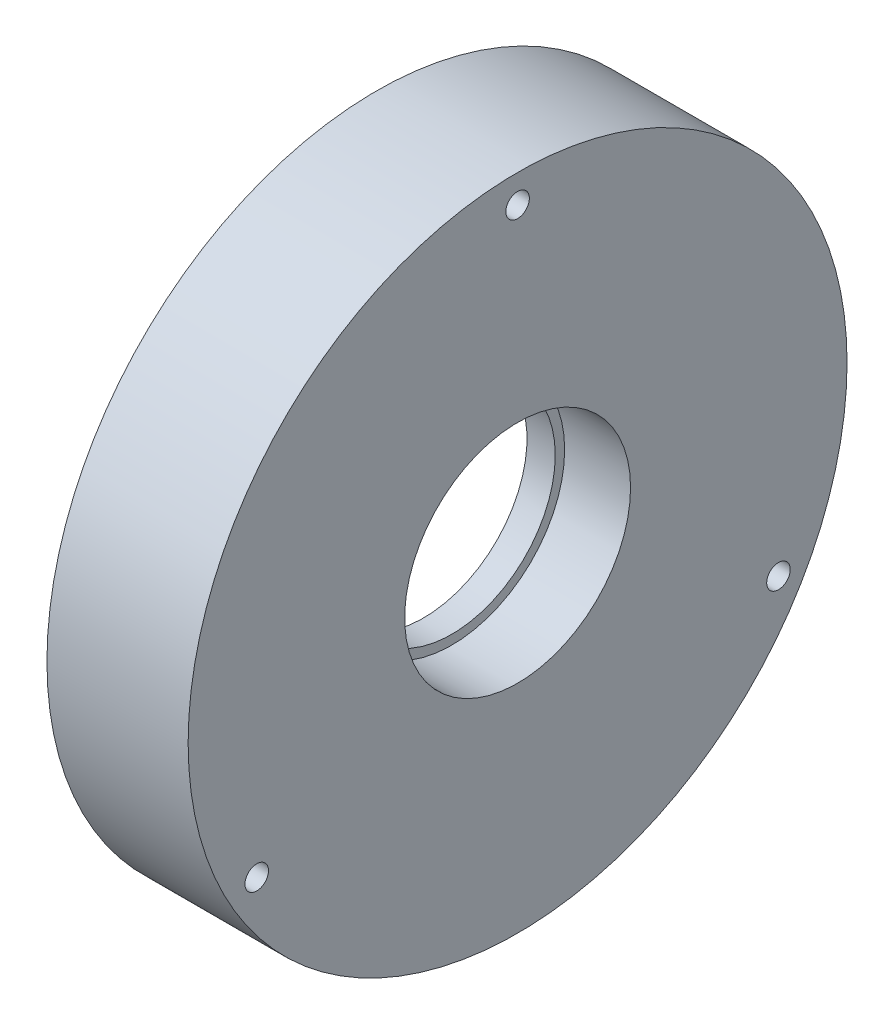
SolidWorks part; units mm, degrees
ref_plane "Plane1" through (0, 0, 0) normal (0, 0, 1) x (1, 0, 0)
ref_plane "Plane2" through (0, 0, 0) normal (0, 1, 0) x (1, 0, 0)
ref_plane "Plane3" through (0, 0, 0) normal (1, 0, 0) x (0, 0, -1)
sketch "HoldingSke" plane through (0, 0, 0) normal (0, 1, 0) x (1, 0, 0)
  line L0 (0, 0) -> (1.1472, -1.6383)
  line L1 (-15, 0) -> (100, 0) construction
  line L2 (0, 0) -> (-2.1039, 2.3779)
  line L3 (0, 0) -> (-11.863, 4.5341)
  line L4 (0, 0) -> (4.9534, 7.0742)
  line L5 (0, 0) -> (-23.7986, -8.8762)
  line L6 (0, 0) -> (-10.5278, -7.1032)
  line L7 (-2.1039, 2.3779) -> (3.3635, 27.1825)
  line L8 (-76.2, 2.8779) -> (-54.61, 2.8779)
  line L9 (-71.009, 38.7566) -> (-53.1078, 45.2721)
  line L10 (-76.2, 71.12) -> (104.1128, 71.12)
  line L11 (0, 0) -> (-5, 0)
  line L12 (-76.2, 101.6) -> (-76.181, 101.6)
  line L13 (24.9733, 27.94) -> (52.9518, 28.4284)
  line L14 (24.9733, 27.94) -> (24.9743, 27.94)
  line L15 (24.9733, 27.94) -> (100.4006, 29.5858)
  circle A0 centre (0, 0) radius 17.5
  circle A1 centre (0, 0) radius 12.7
  circle A2 centre (0, 0) radius 12.7
  dimension "MHD" = 25.4
  dimension "Hub_dia" = 25.4
  dimension "Diameter" = 35
  dimension "Num_teeth" = 55
  dimension "Pitch" = 2
  dimension "Overall_len" = 25.4
  dimension "Show_teeth" = 55
  dimension "Thickness" = 12.7
  dimension "OAL" = 25.4001
  dimension "T_dim" = 21.59
  dimension "Ap" = 20
  dimension "H" = 19.05
  dimension "Pitch_radius" = 180.3128
  dimension "Width" = 5
  dimension "Backlash" = 0.019
  dimension "Addendum_fac" = 1
  dimension "Dedendum_fac" = 1.25
  dimension "Clearance_fac" = 0.25
  dimension "Dedendum_add" = 0.001
  dimension "Module" = 0.5
sketch "BasProSke" plane through (0, 0, 0) normal (0, 1, 0) x (1, 0, 0)
  line L0 (-10, 0) -> (60, 0) construction
  line L1 (0, 13.25) -> (0, 17.5)
  line L2 (0, 13.25) -> (5, 13.25)
  line L3 (5, 13.25) -> (5, 17.5)
  line L4 (5, 17.5) -> (0, 17.5)
  dimension "Diameter" = 35
  dimension "Thickness" = 5
  dimension "Inside_diameter" = 26.5
revolve "Base-Revolve" add sketch "BasProSke" angle 360 about L0
sketch "TooCutSke" plane through (0, 0, 0) normal (1, 0, 0) x (0, 0, -1)
  line L3 (0.4401, 13.743) -> (0.4401, 53.6633) construction
  line L4 (0, 0) -> (0, 59.563) construction
  line L5 (0, 0) -> (-3.9007, 68.2161) construction
  line L6 (-5.9882, 11.3053) -> (37.1172, 13.7701) construction
  circle A0 centre (0, 0) radius 13.75 construction
  circle A1 centre (0, 0) radius 14.376 construction
  circle A2 centre (0, 0) radius 11.6287 construction
  circle A3 centre (0, 0) radius 13.2246 construction
  arc A4 (0.6177, 13.2102) -> (0.1634, 14.3751) centre (-5.9882, 11.3053) ccw
  arc A5 (0.6177, 13.2102) -> (-0.6177, 13.2102) centre (0, 0) ccw
  arc A6 (0.1634, 14.3751) -> (-0.1634, 14.3751) centre (0, 0) ccw
  arc A7 (-0.1634, 14.3751) -> (-0.6177, 13.2102) centre (5.9882, 11.3053) ccw
  dimension "Pitch_dia" = 27.5
  dimension "Base_dia" = 23.2574
  dimension "Root_dia" = 28.752
  dimension "Overcut_dia" = 26.4492
  dimension "Flank_rad" = 6.875
  dimension "Half_ang" = 3.273
  dimension "Half_CT" = 0.4401
extrude "ToothCut" cut sketch "TooCutSke" along normal through all
fillet "Breaks" [suppressed] radius 0.05
fillet "RootFillets" [suppressed] radius 0.126
pattern_circular "TeethCuts" count 55 every 6.545 about axis through (-10, 0, 0) along (1, 0, 0) of "RootFillets", "Breaks", "ToothCut"
sketch "Sketch1" plane through (5, 0, 0) normal (1, 0, 0) x (0, 0, -1)
  circle A0 centre (0, 0) radius 17.5
  circle A1 centre (0, 0) radius 5.5
  dimension "D1" = 11
extrude "Boss-Extrude1" add sketch "Sketch1" along normal blind 2.5
sketch "Sketch2" plane through (5, 0, 0) normal (-1, 0, 0) x (0, 0, 1)
  circle A0 centre (0, 0) radius 5.5
  circle A1 centre (0, 0) radius 7.75
  dimension "D1" = 11
  dimension "D2" = 15.5
extrude "Boss-Extrude2" add sketch "Sketch2" along normal blind 2.5
sketch "Sketch3" plane through (7.5, 0, 0) normal (1, 0, 0) x (0, 0, -1)
  circle A0 centre (0, 0) radius 6
  dimension "D1" = 12
extrude "Cut-Extrude1" cut sketch "Sketch3" against normal blind 3.5
hole_wizard "M1.6 Tapped Hole1" positions "Sketch5" profile "Sketch6" tap size "M1.6" standard "ISO" end condition through all
sketch "Sketch5" plane through (7.5, 0, 0) normal (1, 0, 0) x (0, 0, -1)
  line L2 (0, 19.3966) -> (0, 0) construction
  point P0 (0, 16)
  dimension "D1" = 16
cosmetic thread "Hole Thread1" parameters "D2"=1.6
sketch "Sketch6" plane through (7.5, 16, 0) normal (0, 1, 0) x (0, 0, -1)
  line L0 (0, 0) -> (0, 7.5)
  line L1 (0, 7.5) -> (0.625, 7.5)
  line L2 (0.625, 7.5) -> (0.625, 0)
  line L5 (0.625, 0) -> (0, 0)
  line L11 (0, -6.35) -> (0, 107.95) construction
  dimension "Thru Tap Drill Dia." = 1.25
  dimension "Thru Tap Drill Depth" = 7.5
pattern_circular "CirPattern1" count 3 over 360 about axis through (0, 0, 0) along (1, 0, 0) of "M1.6 Tapped Hole1"
equation "' \"Module@HoldingSke\" = 6.35"
equation "' \"Num_teeth@HoldingSke\" = 24"
equation "' \"Ap@HoldingSke\" =  14.5"
equation "' \"Ap@HoldingSke\" = 14.5"
equation "' \"Width@HoldingSke\" = 12"
equation "' \"Diameter@HoldingSke\" = 8 * 25.4"
equation "' \"Show_teeth@HoldingSke\" = 100"
equation "' \"Backlash@HoldingSke\" = 0.009 * 25.4"
equation "' \"Addendum_fac@HoldingSke\" = 1.0"
equation "' \"Dedendum_fac@HoldingSke\" = 1.25"
equation "' \"Dedendum_add@HoldingSke\" = 0.00005 * 25.4"
equation "' \"Clearance_fac@HoldingSke\" = 0.25"
equation "\"Pitch@HoldingSke\" = 1 / \"Module@HoldingSke\" "
equation "\"Overcut_dia@TooCutSke\" = (\"Num_teeth@HoldingSke\" - 2 * \"Addendum_fac@HoldingSke\") / \"Pitch@HoldingSke\" - 0.002 * 25.4"
equation "\"Pitch_dia@TooCutSke\" = \"Num_teeth@HoldingSke\" / \"Pitch@HoldingSke\""
equation "\"Base_dia@TooCutSke\" = \"Num_teeth@HoldingSke\" / \"Pitch@HoldingSke\" * cos((\"Ap@HoldingSke\"  * 3.14159265 / 180)) * 0.90"
equation "\"Root_dia@TooCutSke\" = \"Num_teeth@HoldingSke\"  / \"Pitch@HoldingSke\" + 2 *  \"Dedendum_fac@HoldingSke\"/ \"Pitch@HoldingSke\" + \"Dedendum_add@HoldingSke\" * 2"
equation "\"Half_ang@TooCutSke\" = 180 / \"Num_teeth@HoldingSke\""
equation "\"Half_CT@TooCutSke\" = \"Num_teeth@HoldingSke\" / \"Pitch@HoldingSke\" * sin((3.14159265 / 2 / \"Num_teeth@HoldingSke\")) / 2 + 10 * \"Backlash@HoldingSke\" / 4"
equation "\"Flank_rad@TooCutSke\" = \"Num_teeth@HoldingSke\" / \"Pitch@HoldingSke\" / 4"
equation "\"Radius@RootFillets\"= \"Clearance_fac@HoldingSke\" / \"Pitch@HoldingSke\" + \"Dedendum_add@HoldingSke\""
equation "\"Break_rad@Breaks\" = 0.02 / \"Pitch@HoldingSke\" * 5"
equation "\"Num_teeth@TeethCuts\" = int( \"Show_teeth@HoldingSke\" ) + 1"
equation "\"Num_teeth@TeethCuts\" = ((sgn( \"Num_teeth@TeethCuts\" - \"Num_teeth@HoldingSke\" )-1)*( \"Num_teeth@TeethCuts\" - \"Num_teeth@HoldingSke\" ))/-2+ \"Num_teeth@HoldingSke\""
equation "\"Num_teeth@TeethCuts\" = ((sgn( \"Num_teeth@TeethCuts\" - 2.0)+1)*( \"Num_teeth@TeethCuts\" - 2.0))/2 +2.0"
equation "\"Angle@TeethCuts\" = 360.0 / \"Num_teeth@HoldingSke\""
equation "\"Diameter@BasProSke\" = \"Num_teeth@HoldingSke\"  / \"Pitch@HoldingSke\" + 2 *  \"Dedendum_fac@HoldingSke\"/ \"Pitch@HoldingSke\" + \"Dedendum_add@HoldingSke\" * 2 + 0.002 * 25.4"
equation "\"Diameter@BasProSke\" = ((sgn( \"Diameter@BasProSke\"  - \"Diameter@HoldingSke\" )+1)*( \"Diameter@BasProSke\"  - \"Diameter@HoldingSke\" ))/2 + \"Diameter@HoldingSke\""
equation "\"Inside_diameter@BasProSke\" =  (\"Num_teeth@HoldingSke\" - 2 * \"Addendum_fac@HoldingSke\") / \"Pitch@HoldingSke\" "
equation "\"Thickness@BasProSke\"  = \"Width@HoldingSke\""
